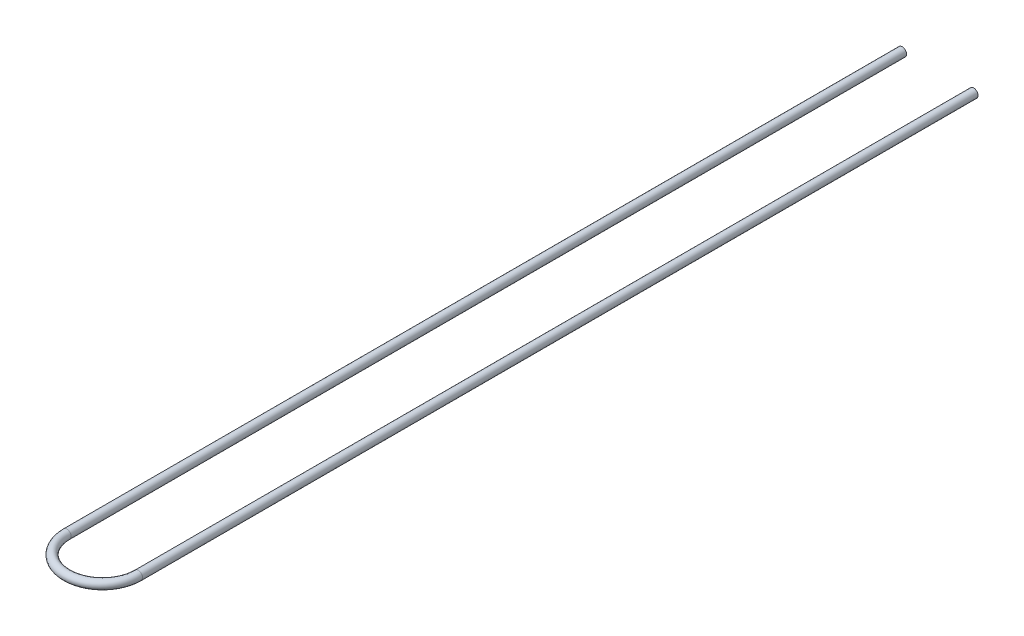
SolidWorks part; units mm, degrees
ref_plane "Front Plane" through (0, 0, 0) normal (0, 0, 1) x (1, 0, 0)
ref_plane "Top Plane" through (0, 0, 0) normal (0, 1, 0) x (1, 0, 0)
ref_plane "Right Plane" through (0, 0, 0) normal (1, 0, 0) x (0, 0, -1)
sketch "Sketch1" plane through (0, 0, 0) normal (0, 1, 0) x (1, 0, 0)
  line L0 (143.08, -300) -> (143.08, -2440)
  line L2 (-40, -300) -> (-40, -2440)
  arc A0 (-40, -2440) -> (143.08, -2440) centre (51.54, -2440) ccw
  dimension "D1" = 2140
  dimension "D2" = 183.08
ref_plane "Plane1" through (143.08, 0, 300) normal (0, 0, -1) x (-1, 0, 0)
sketch "Sketch2" plane through (143.08, 0, 300) normal (0, 0, -1) x (-1, 0, 0)
  circle A0 centre (0, 0) radius 9.95
  circle A1 centre (0, 0) radius 11.1
  dimension "D1" = 22.2
  dimension "D2" = 19.9
sweep "Sweep1" add profiles "Sketch2" path "Sketch1"
